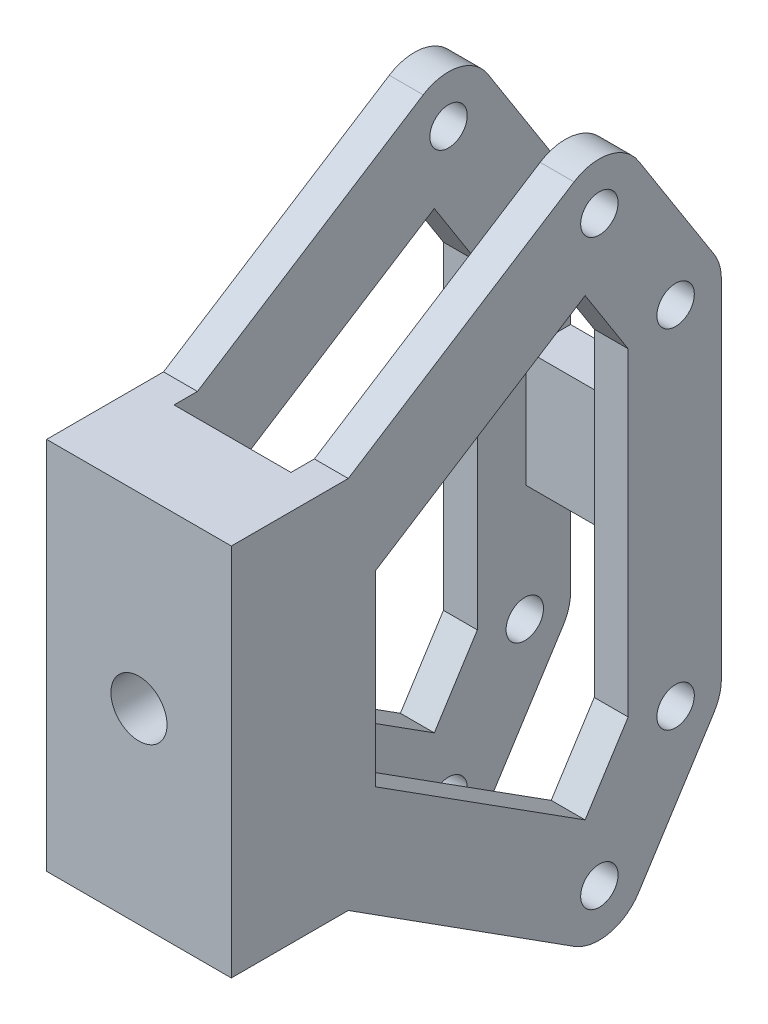
SolidWorks part; units mm, degrees
ref_plane "Front Plane" through (0, 0, 0) normal (0, 0, 1) x (1, 0, 0)
ref_plane "Top Plane" through (0, 0, 0) normal (0, 1, 0) x (1, 0, 0)
ref_plane "Right Plane" through (0, 0, 0) normal (1, 0, 0) x (0, 0, -1)
sketch "Sketch1" plane through (0, 0, 0) normal (1, 0, 0) x (0, 0, -1)
  line L0 (0, -40) -> (0, 40)
  line L1 (0, 40) -> (25, 40)
  line L2 (25, 40) -> (73.2801, 70.7854)
  line L3 (87.0883, 67.7301) -> (103.2229, 42.4264)
  line L4 (104.7912, 37.05) -> (104.7912, -37.05)
  line L5 (-32.2378, 0) -> (212.0044, 0) construction
  line L6 (30.81, -20) -> (30.81, 20)
  line L7 (30.81, 20) -> (75.6511, 48.5528)
  line L8 (75.6511, 48.5528) -> (84.8572, 34.095)
  line L9 (84.8572, 34.095) -> (84.8572, -34.095)
  line L10 (75.6511, -48.5528) -> (84.8572, -34.095)
  line L11 (30.81, -20) -> (75.6511, -48.5528)
  line L12 (87.0883, -67.7301) -> (103.2229, -42.4264)
  line L13 (25, -40) -> (73.2801, -70.7854)
  line L14 (0, -40) -> (25, -40)
  arc A0 (73.2801, 70.7854) -> (87.0883, 67.7301) centre (78.6565, 62.3536) cw
  arc A1 (103.2229, 42.4264) -> (104.7912, 37.05) centre (94.7912, 37.05) cw
  circle A3 centre (78.7, 62.25) radius 4
  circle A4 centre (95, 37.1536) radius 4
  circle A5 centre (95, -37.1536) radius 4
  circle A6 centre (78.7, -62.25) radius 4
  arc A7 (103.2229, -42.4264) -> (104.7912, -37.05) centre (94.7912, -37.05) ccw
  arc A8 (73.2801, -70.7854) -> (87.0883, -67.7301) centre (78.6565, -62.3536) ccw
  point P15 (0, 0)
  point P24 (84.8572, 0)
  point P25 (30.81, 0)
  point P26 (104.7912, 0)
  point P27 (0, 0)
  dimension "D4" = 10
  dimension "D6" = 10
  dimension "D15" = 8
  dimension "D18" = 8
  dimension "D1" = 40
  dimension "D2" = 25
  dimension "D3" = 57.26
  dimension "D5" = 30.01
  dimension "D7" = 37.05
  dimension "D8" = 30.81
  dimension "D9" = 20
  dimension "D10" = 53.16
  dimension "D11" = 17.14
  dimension "D12" = 34.095
  dimension "D13" = 22.25
  dimension "D14" = 78.7
  dimension "D16" = 25.2
  dimension "D17" = 95
extrude "Boss-Extrude1" add sketch "Sketch1" along normal blind 39.5
sketch "Sketch2" plane through (0, 0, 0) normal (0, 1, 0) x (1, 0, 0)
  line L0 (19.75, 0) -> (19.75, 126.714) construction
  line L1 (39.5, 0) -> (0, 0) construction
  line L3 (7.25, 95.25) -> (32.25, 95.25)
  line L4 (7.25, 95.25) -> (7.25, 20)
  line L5 (7.25, 20) -> (32.25, 20)
  line L6 (32.25, 95.25) -> (32.25, 20)
  line L7 (7.25, 95.25) -> (32.25, 20) construction
  line L8 (7.25, 20) -> (32.25, 95.25) construction
  point P4 (19.75, 57.625)
  dimension "D1" = 75.25
  dimension "D2" = 25
  dimension "D3" = 20
extrude "Cut-Extrude1" cut sketch "Sketch2" against normal blind 117.5 and the other way blind 105.5
sketch "Sketch3" plane through (0, 0, -104.7912) normal (0, 0, -1) x (-1, 0, 0)
  line L2 (-39.5, -37.05) -> (0, -37.05) construction
  line L3 (-7.25, -37.05) -> (-7.25, -12.5)
  line L4 (-7.25, -12.5) -> (-32.25, -12.5)
  line L5 (-32.25, -12.5) -> (-32.25, -37.05)
  line L9 (-39.5, 37.05) -> (0, 37.05) construction
  line L10 (-32.25, 37.05) -> (-32.25, 12.5)
  line L11 (-32.25, 12.5) -> (-7.25, 12.5)
  line L12 (-7.25, 12.5) -> (-7.25, 37.05)
  line L16 (-32.25, 54.9301) -> (-32.25, 37.05)
  line L17 (-7.25, 54.9301) -> (-7.25, 37.05)
  line L18 (-32.25, 54.9301) -> (-7.25, 54.9301)
  line L19 (-32.25, -37.05) -> (-32.25, -54.9301)
  line L20 (-32.25, -54.9301) -> (-7.25, -54.9301)
  line L21 (-7.25, -54.9301) -> (-7.25, -37.05)
  dimension "D5" = 24.55
  dimension "D6" = 24.55
extrude "Cut-Extrude2" cut sketch "Sketch3" against normal blind 43.5
sketch "Sketch4" plane through (0, 0, 0) normal (0, 0, 1) x (1, 0, 0)
  line L1 (19.75, 40) -> (19.75, 55.4414) construction
  line L2 (39.5, 40) -> (0, 40) construction
  line L3 (0, 0) -> (19.75, 0) construction
  line L4 (0, 40) -> (0, -40) construction
  line L5 (19.75, 40) -> (19.75, 0) construction
  circle A1 centre (19.75, 0) radius 6
  dimension "D1" = 12
extrude "Cut-Extrude3" cut sketch "Sketch4" against normal blind 41
scale "Scale1" scale about centroid uniform scaling yes scale factor 0.7
